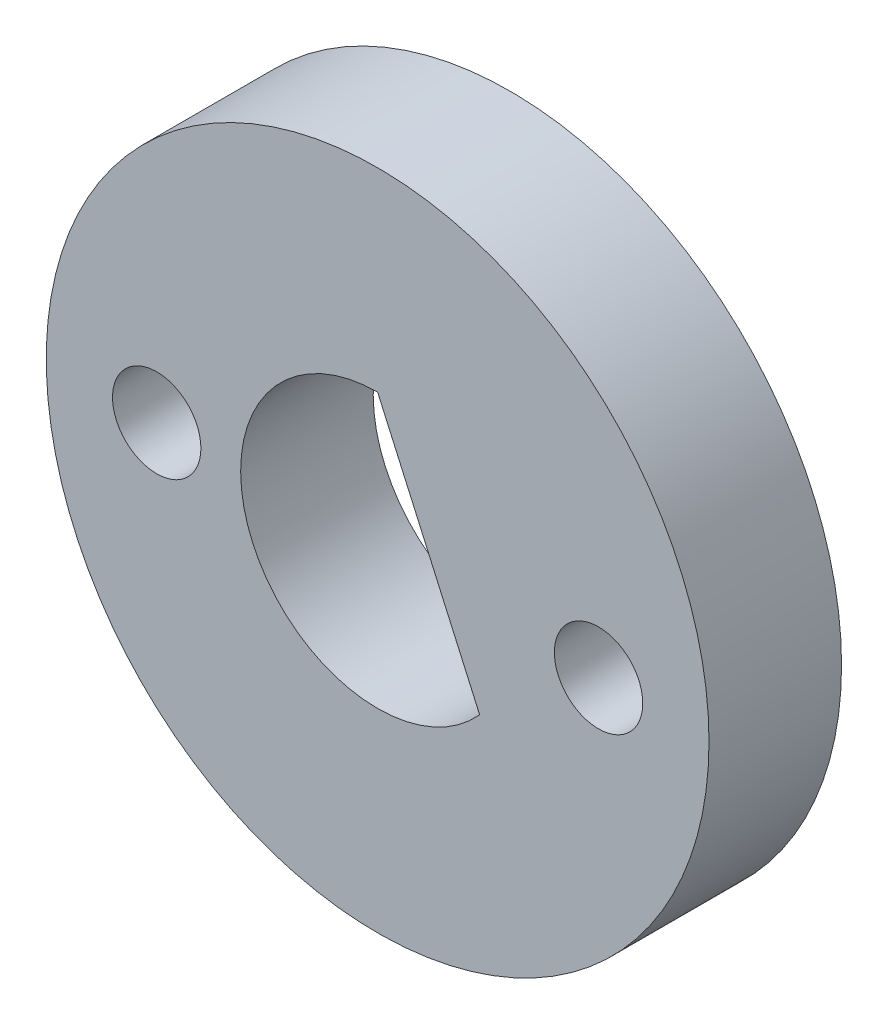
SolidWorks part; units mm, degrees
ref_plane "Front Plane" through (0, 0, 0) normal (0, 0, 1) x (1, 0, 0)
ref_plane "Top Plane" through (0, 0, 0) normal (0, 1, 0) x (1, 0, 0)
ref_plane "Right Plane" through (0, 0, 0) normal (1, 0, 0) x (0, 0, -1)
sketch "Sketch1" plane through (0, 0, 0) normal (0, 0, 1) x (1, 0, 0)
  circle A0 centre (0, 0) radius 7.5
extrude "Boss-Extrude1" add sketch "Sketch1" along normal blind 3
sketch "Sketch2" plane through (0, 0, 3) normal (0, 0, 1) x (1, 0, 0)
  line L0 (0, 3.1) -> (2.3089, -2.0686)
  arc A0 (0, 3.1) -> (2.3089, -2.0686) centre (0, 0) ccw
extrude "Cut-Extrude1" cut sketch "Sketch2" against normal blind 3
hole_wizard "Ø2.0mm Dowel Hole1" positions "Sketch4" profile "Sketch5" hole size "Ø2.0" standard "ANSI Metric"
sketch "Sketch4" plane through (0, 0, 3) normal (0, 0, 1) x (1, 0, 0)
  point P0 (-5, 0)
  point P2 (5, 0)
  dimension "D1" = 5
  dimension "D2" = 5
sketch "Sketch5" plane through (-5, 0, 3) normal (1, 0, 0) x (0, -1, 0)
  line L0 (0, 0) -> (0, 3.5999)
  line L1 (0, 3.5999) -> (1, 2.999)
  line L2 (1, 2.999) -> (1, 0)
  line L5 (1, 0) -> (0, 0)
  line L10 (0, 3.5999) -> (-1, 2.999) construction
  line L11 (0, -6.35) -> (0, 107.95) construction
  dimension "Hole Dia." = 2
  dimension "Hole Depth" = 2.999
  dimension "Drill Angle" = 118
